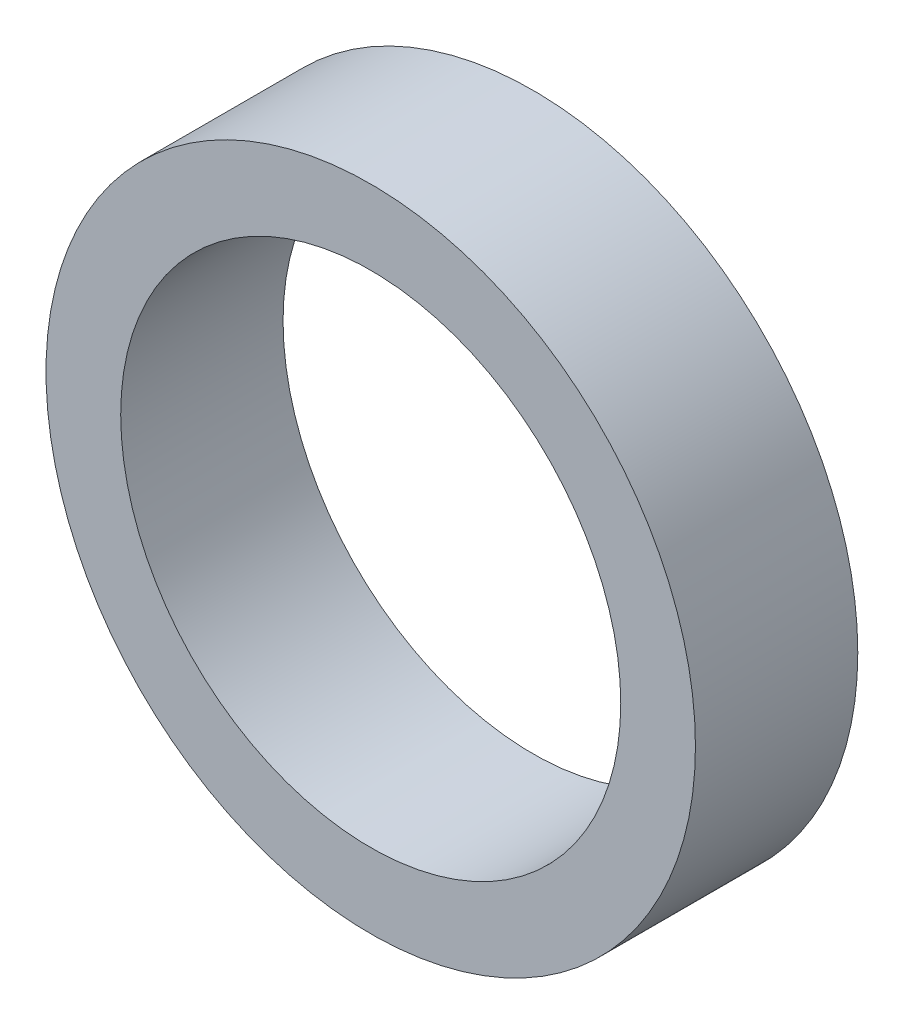
SolidWorks part; units mm, degrees
material "Custom Plastic"
ref_plane "Front Plane" through (0, 0, 0) normal (0, 0, 1) x (1, 0, 0)
ref_plane "Top Plane" through (0, 0, 0) normal (0, 1, 0) x (1, 0, 0)
ref_plane "Right Plane" through (0, 0, 0) normal (1, 0, 0) x (0, 0, -1)
sketch "Sketch1" plane through (0, 0, 0) normal (0, 0, 1) x (1, 0, 0)
  circle A0 centre (0, 0) radius 10
  circle A1 centre (0, 0) radius 7.7
  dimension "D1" = 20
  dimension "D2" = 15.4
extrude "Boss-Extrude1" add sketch "Sketch1" along normal blind 5
